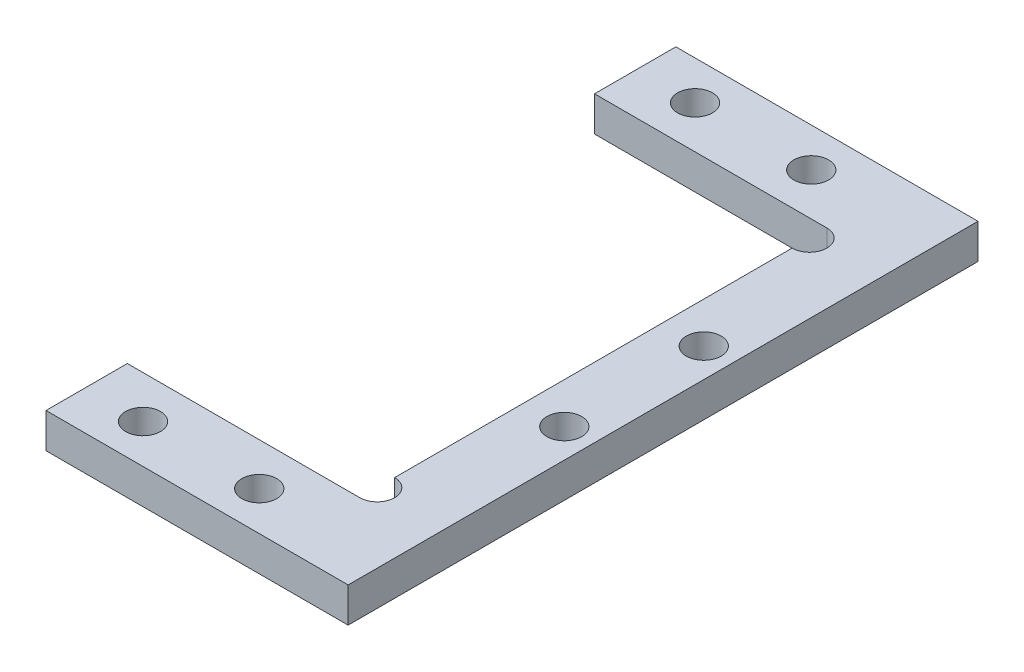
SolidWorks part; units mm, degrees
material "Thornel Mat VMA"
ref_plane "前视基准面" through (0, 0, 0) normal (0, 0, 1) x (1, 0, 0)
ref_plane "上视基准面" through (0, 0, 0) normal (0, 1, 0) x (1, 0, 0)
ref_plane "右视基准面" through (0, 0, 0) normal (1, 0, 0) x (0, 0, -1)
sketch "草图1" plane through (0, 0, 0) normal (0, 1, 0) x (1, 0, 0)
  line L1 (0, 0) -> (-38, 0)
  line L2 (0, 0) -> (0, -7)
  line L3 (0, -7) -> (-38, -7)
  line L4 (-38, 0) -> (-38, -7)
  dimension "D1" = 7
  dimension "D2" = 38
extrude "凸台-拉伸1" add sketch "草图1" along normal blind 3
sketch "草图2" plane through (0, 0, 7) normal (0, 0, 1) x (1, 0, 0)
  line L1 (0, 3) -> (-7, 3)
  line L2 (0, 3) -> (0, 0)
  line L3 (0, 0) -> (-7, 0)
  line L4 (-7, 3) -> (-7, 0)
  line L5 (-38, 0) -> (0, 0) construction
  dimension "D1" = 3
  dimension "D2" = 7
extrude "凸台-拉伸2" add sketch "草图2" along normal blind 13
sketch "草图3" plane through (0, 3, 0) normal (0, 1, 0) x (1, 0, 0)
  line L0 (-3.5, -20) -> (-3.5, -15) construction
  line L1 (0, -20) -> (-7, -20) construction
  line L2 (-3.5, -15) -> (-3.5, -5) construction
  circle A0 centre (-3.5, -15) radius 1.5
  circle A1 centre (-3.5, -5) radius 1.5
  dimension "D3" = 3
  dimension "D4" = 3
  dimension "D1" = 5
  dimension "D2" = 10
extrude "切除-拉伸1" cut sketch "草图3" against normal through all
sketch "草图4" plane through (0, 3, 0) normal (0, 1, 0) x (1, 0, 0)
  line L0 (-38, -7) -> (-38, -3.65) construction
  line L3 (-38, -3.65) -> (-33, -3.65) construction
  line L4 (-33, -3.65) -> (-23, -3.65) construction
  circle A0 centre (-33, -3.65) radius 1.5
  circle A1 centre (-23, -3.65) radius 1.5
  dimension "D3" = 3
  dimension "D4" = 3
  dimension "D1" = 5
  dimension "D2" = 10
extrude "切除-拉伸2" cut sketch "草图4" against normal through all
sketch "草图5" plane through (0, 3, 0) normal (0, 1, 0) x (1, 0, 0)
  line L0 (-38, 0) -> (-18, 0) construction
  line L1 (0, 0) -> (-38, 0) construction
  line L3 (-18, 0) -> (-13, 0)
  line L4 (-18, 0) -> (-18, 40.2)
  line L5 (-18, 40.2) -> (-13, 40.2)
  line L6 (-13, 0) -> (-13, 40.2)
  dimension "D1" = 20
  dimension "D2" = 40.2
  dimension "D3" = 5
extrude "凸台-拉伸3" add sketch "草图5" against normal blind 3
sketch "草图6" plane through (0, 3, 0) normal (0, 1, 0) x (1, 0, 0)
  line L0 (-18, 40.2) -> (-18, 0) construction
  line L1 (-18, 0) -> (-38, 0) construction
  circle A0 centre (-18, 1.5) radius 1.5
  dimension "D1" = 3
extrude "切除-拉伸3" cut sketch "草图6" against normal through all
fillet "圆角1" radius 5 1 edges at (-7, 1.5, 7)
fillet "圆角2" radius 5 1 edges at (-13, 1.5, 0)
ref_plane "基准面1" through (0, 0, -20.1) normal (0, 0, -1) x (-1, 0, 0)
mirror "镜向1" about plane through (0, 0, -20.1) normal (0, 0, -1) of "圆角2", "切除-拉伸3", "凸台-拉伸1", "切除-拉伸2"
sketch "草图7" plane through (0, 0, 0) normal (1, 0, 0) x (0, 0, -1)
  line L1 (47.2, 0) -> (-25.8968, 0)
  line L2 (47.2, 0) -> (47.2, 5.1184)
  line L3 (47.2, 5.1184) -> (-25.8968, 5.1184)
  line L4 (-25.8968, 0) -> (-25.8968, 5.1184)
extrude "切除-拉伸4" cut sketch "草图7" against normal blind 13
sketch "草图9" plane through (-13, 0, 0) normal (1, 0, 0) x (0, 0, -1)
  line L1 (-7, 3) -> (47.2, 3)
  line L2 (-7, 3) -> (-7, 0)
  line L3 (-7, 0) -> (47.2, 0)
  line L4 (47.2, 3) -> (47.2, 0)
extrude "凸台-拉伸4" add sketch "草图9" along normal blind 1
sketch "草图8" plane through (0, 3, 0) normal (0, 1, 0) x (1, 0, 0)
  line L3 (-14.5, 20.1) -> (-14.5, 14.1) construction
  line L4 (-14.5, 14.1) -> (-14.5, 26.1) construction
  line L5 (-18, 37.2) -> (-18, 3) construction
  circle A0 centre (-14.5, 14.1) radius 1.5
  circle A1 centre (-14.5, 26.1) radius 1.5
  dimension "D3" = 3
  dimension "D4" = 3
  dimension "D1" = 6
  dimension "D2" = 12
  dimension "D5" = 3.5
extrude "切除-拉伸5" cut sketch "草图8" against normal through all
